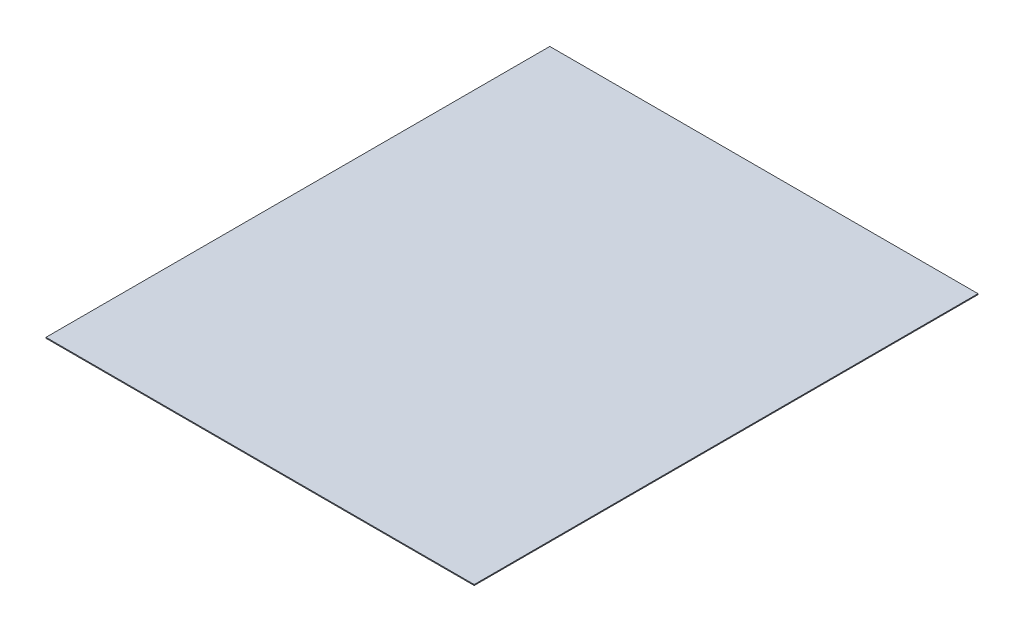
SolidWorks part; units mm, degrees
ref_plane "Front Plane" through (0, 0, 0) normal (0, 0, 1) x (1, 0, 0)
ref_plane "Top Plane" through (0, 0, 0) normal (0, 1, 0) x (1, 0, 0)
ref_plane "Right Plane" through (0, 0, 0) normal (1, 0, 0) x (0, 0, -1)
other "Configuration Table"
sketch "Sketch1" plane through (0, 0, 0) normal (0, 0, 1) x (1, 0, 0)
  line L1 (1.5, 1968.5) -> (698.5, 1968.5)
  line L2 (1.5, 1968.5) -> (1.5, 1970)
  line L3 (1.5, 1970) -> (698.5, 1970)
  line L4 (698.5, 1968.5) -> (698.5, 1970)
extrude "PACK_dis_ust_1" add sketch "Sketch1" against normal blind 820 separate body
